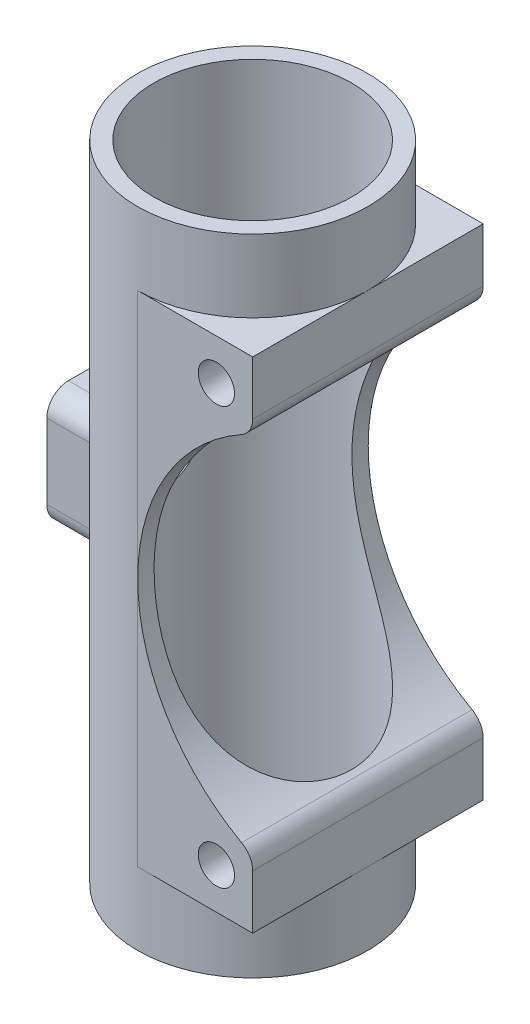
SolidWorks part; units mm, degrees
material "6061-T6 (SS)"
ref_plane "Front Plane" through (0, 0, 0) normal (0, 0, 1) x (1, 0, 0)
ref_plane "Top Plane" through (0, 0, 0) normal (0, 1, 0) x (1, 0, 0)
ref_plane "Right Plane" through (0, 0, 0) normal (1, 0, 0) x (0, 0, -1)
sketch "Sketch1" plane through (0, 0, 0) normal (0, 1, 0) x (1, 0, 0)
  circle A0 centre (0, 0) radius 10.9
  circle A1 centre (0, 0) radius 12.7
  dimension "D1" = 21.8
  dimension "D2" = 25.4
extrude "Boss-Extrude1" add sketch "Sketch1" along normal blind 71
sketch "Sketch2" plane through (0, 0, 0) normal (0, -1, 0) x (1, 0, 0)
  line L0 (0, 12.7) -> (12.7, 12.7)
  line L1 (12.7, 12.7) -> (12.7, -12.7)
  line L2 (12.7, -12.7) -> (0, -12.7)
  arc A0 (0, -12.7) -> (0, 12.7) centre (0, 0) ccw
  circle M1 centre (0, 0) radius 12.7
extrude "Boss-Extrude2" add sketch "Sketch2" against normal blind 63 contours L1 L0 M1 | L2 L1 M1
sketch "Sketch3" plane through (0, 0, 0) normal (0, -1, 0) x (1, 0, 0)
  line L0 (0, 12.7) -> (12.7, 12.7)
  line L1 (12.7, 12.7) -> (12.7, -12.7) construction
  line L2 (0, 12.7) -> (12.7, 12.7) construction
  line L3 (12.7, 12.7) -> (12.7, -12.7)
  line L4 (12.7, -12.7) -> (0, -12.7)
  arc A0 (0, -12.7) -> (0, 12.7) centre (0, 0) ccw
  line M2 (0, -12.7) -> (12.7, -12.7)
  line M3 (12.7, -12.7) -> (12.7, 12.7)
  line M4 (12.7, 12.7) -> (0, 12.7)
extrude "Cut-Extrude1" cut sketch "Sketch3" against normal blind 8 contours A0 L3 M4 | A0 M2 M3
sketch "Sketch4" plane through (0, 0, 0) normal (0, 0, 1) x (1, 0, 0)
  line L3 (12.7, 63) -> (12.7, 8) construction
  line L5 (10.4999, 35.5) -> (10.4999, 54.4) construction
  line L6 (10.4999, 35.5) -> (10.4999, 16.6) construction
  circle A3 centre (22.3312, 35.5) radius 22.2977
extrude "Cut-Extrude2" cut sketch "Sketch4" against normal blind 16 and the other way blind 15
sketch "Sketch5" plane through (0, 0, -12.7) normal (0, 0, -1) x (-1, 0, 0)
  line L0 (-12.7, 63) -> (-8.7, 63) construction
  line L1 (0, 63) -> (-12.7, 63) construction
  line L2 (-8.7, 63) -> (-8.7, 58.5) construction
  line L3 (-12.7, 8) -> (-8.7, 8) construction
  line L4 (-12.7, 8) -> (0, 8) construction
  line L5 (-8.7, 8) -> (-8.7, 12.5) construction
  circle A0 centre (-8.7, 58.5) radius 2
  circle A1 centre (-8.7, 12.5) radius 2
  dimension "D1" = 4.5
  dimension "D2" = 4
  dimension "D3" = 4
  dimension "D4" = 4.5
  dimension "D5" = 4
  dimension "D6" = 4
extrude "Cut-Extrude3" cut sketch "Sketch5" against normal blind 4
sketch "Sketch6" plane through (0, 0, 12.7) normal (0, 0, 1) x (1, 0, 0)
  line L0 (12.7, 63) -> (8.7, 63) construction
  line L1 (12.7, 63) -> (0, 63) construction
  line L2 (8.7, 63) -> (8.7, 58.5) construction
  line L3 (12.7, 8) -> (8.7, 8) construction
  line L4 (12.7, 8) -> (0, 8) construction
  line L5 (8.7, 8) -> (8.7, 12.5) construction
  circle A0 centre (8.7, 58.5) radius 2
  circle A1 centre (8.7, 12.5) radius 2
  dimension "D1" = 4
  dimension "D3" = 4
  dimension "D2" = 4.5
  dimension "D4" = 4.5
extrude "Cut-Extrude4" cut sketch "Sketch6" against normal blind 4
ref_plane "Plane1" through (0, 35.5, 0) normal (0, 1, 0) x (1, 0, 0)
sketch "Sketch14" plane through (0, 35.5, 0) normal (0, 1, 0) x (1, 0, 0)
  line L1 (-14.4365, -6.5) -> (-14.4365, 6.5)
  line L4 (-14.4365, 6.5) -> (-10.8366, 6.5)
  line L5 (-14.4365, -6.5) -> (-10.8366, -6.5)
  arc A1 (-10.8366, 6.5) -> (-10.8366, -6.5) centre (0, 0) ccw
  point P7 (-14.4365, 0)
extrude "Boss-Extrude3" add sketch "Sketch14" along normal blind 6.5 and the other way blind 6.5
sketch "Sketch15" plane through (-14.4365, 0, 0) normal (-1, 0, 0) x (0, 0, 1)
  line L0 (13.97, 35.5) -> (-13.97, 35.5) construction
  circle A0 centre (0, 35.5) radius 4
extrude "Cut-Extrude14" cut sketch "Sketch15" against normal blind 7.5
sketch "Sketch16" plane through (-14.4365, 0, 0) normal (-1, 0, 0) x (0, 0, 1)
  line L4 (6.5, 29) -> (6.5, 42)
  line L5 (6.5, 29) -> (6.5, 42)
  line L6 (-6.5, 42) -> (-6.5, 29)
  line L7 (-6.5, 42) -> (-6.5, 29)
  line L9 (6.5, 42) -> (-6.5, 42)
  line L11 (-6.5, 29) -> (6.5, 29)
  line L13 (6.5, 42) -> (-6.5, 42)
  line L15 (-6.5, 29) -> (6.5, 29)
  circle A2 centre (0, 35.5) radius 4
  circle A3 centre (0, 35.5) radius 4
  dimension "D1" = 0
  dimension "D2" = 0
extrude "Boss-Extrude4" add sketch "Sketch16" along normal blind 1.75
fillet "Fillet1" radius 2.38 4 edges at (-13.5485, 42, 6.5) (-13.5485, 29, 6.5) (-13.5485, 29, -6.5) (-13.5485, 42, -6.5)
fillet "Fillet2" radius 2.38 2 edges at (12.7, 55.6104, 0) (12.7, 15.3896, 0)
